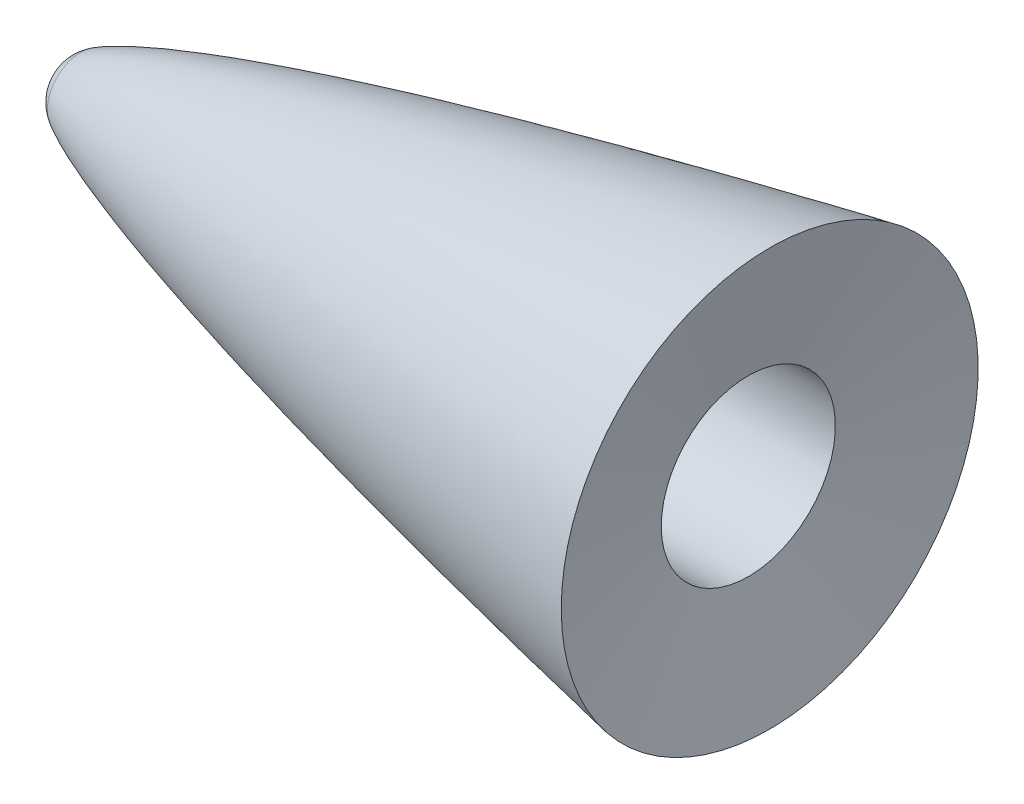
SolidWorks part; units mm, degrees
ref_plane "Front Plane" through (0, 0, 0) normal (0, 0, 1) x (1, 0, 0)
ref_plane "Top Plane" through (0, 0, 0) normal (0, 1, 0) x (1, 0, 0)
ref_plane "Right Plane" through (0, 0, 0) normal (1, 0, 0) x (0, 0, -1)
sketch "Sketch1" plane through (0, 0, 0) normal (0, 0, 1) x (1, 0, 0)
  line L0 (50.8, 15.2019) -> (73.2006, 19.4568) construction
  line L1 (33.9089, 0) -> (-0.8133, 0)
  line L2 (0, 0) -> (105.8025, 0) construction
  line L3 (49.2392, 6.35) -> (36.5392, 6.35)
  line L4 (49.2392, 6.35) -> (50.8, 15.2019)
  line L5 (36.5392, 6.35) -> (33.9089, 0)
  arc A0 (0.5561, 2.4364) -> (-0.8133, 0) centre (2.0388, 0) ccw
  spline S0 degree 4 poles (0, 1.985) (0.0037, 1.9958) (0.0128, 2.0142) (0.0311, 2.0377) (0.0591, 2.0699) (0.0955, 2.1062) (0.149, 2.1544) (0.2348, 2.2233) (0.3767, 2.325) (0.617, 2.4775) (1.0234, 2.7054) (1.7303, 3.0532) (2.8301, 3.5279) (4.7428, 4.2585) (7.4066, 5.1514) (10.6919, 6.1417) (14.4555, 7.1831) (18.2622, 8.1681) (22.045, 9.0983) (25.8949, 10.0013) (29.6578, 10.8541) (33.5814, 11.7094) (37.2558, 12.4919) (41.3537, 13.3342) (44.7623, 14.0242) (48.9323, 14.8421) (51.2754, 15.2947) (53.5303, 15.7244) (55.0889, 16.0199) (55.4404, 16.0847) (55.9224, 16.176) knots 0 0 0 0 0 0.000788 0.001421 0.002041 0.002962 0.004334 0.006402 0.009642 0.015039 0.023992 0.038642 0.064061 0.097932 0.165424 0.233167 0.300909 0.368651 0.436394 0.504136 0.571878 0.639621 0.707363 0.775105 0.842848 0.91059 0.955295 0.977647 1 1 1 1 1 construction
  spline S1 degree 4 poles (0.5561, 2.4364) (0.5874, 2.4554) (0.73, 2.5406) (1.0606, 2.7237) (1.7303, 3.0532) (2.8301, 3.5279) (4.7428, 4.2585) (7.4066, 5.1514) (10.6919, 6.1417) (14.4555, 7.1831) (18.2622, 8.1681) (22.045, 9.0983) (25.8949, 10.0013) (29.6578, 10.8541) (33.5814, 11.7094) (37.2558, 12.4919) (41.3537, 13.3342) (44.7623, 14.0242) (48.1804, 14.6946) (49.9242, 15.0332) (50.8, 15.2019) knots 0.012503 0.012503 0.012503 0.012503 0.012503 0.015039 0.023992 0.038642 0.064061 0.097932 0.165424 0.233167 0.300909 0.368651 0.436394 0.504136 0.571878 0.639621 0.707363 0.775105 0.842848 0.91059 0.91059 0.91059 0.91059 0.91059
  point P6 (0, 0)
  dimension "D1" = 12.7
  dimension "D2" = 100
  dimension "D3" = 10.755
  dimension "D4" = 15.2019
  dimension "D5" = 50.8
  dimension "D6" = 67.5
  dimension "D7" = 6.35
revolve "Revolve1" add sketch "Sketch1" angle 360 about L2
